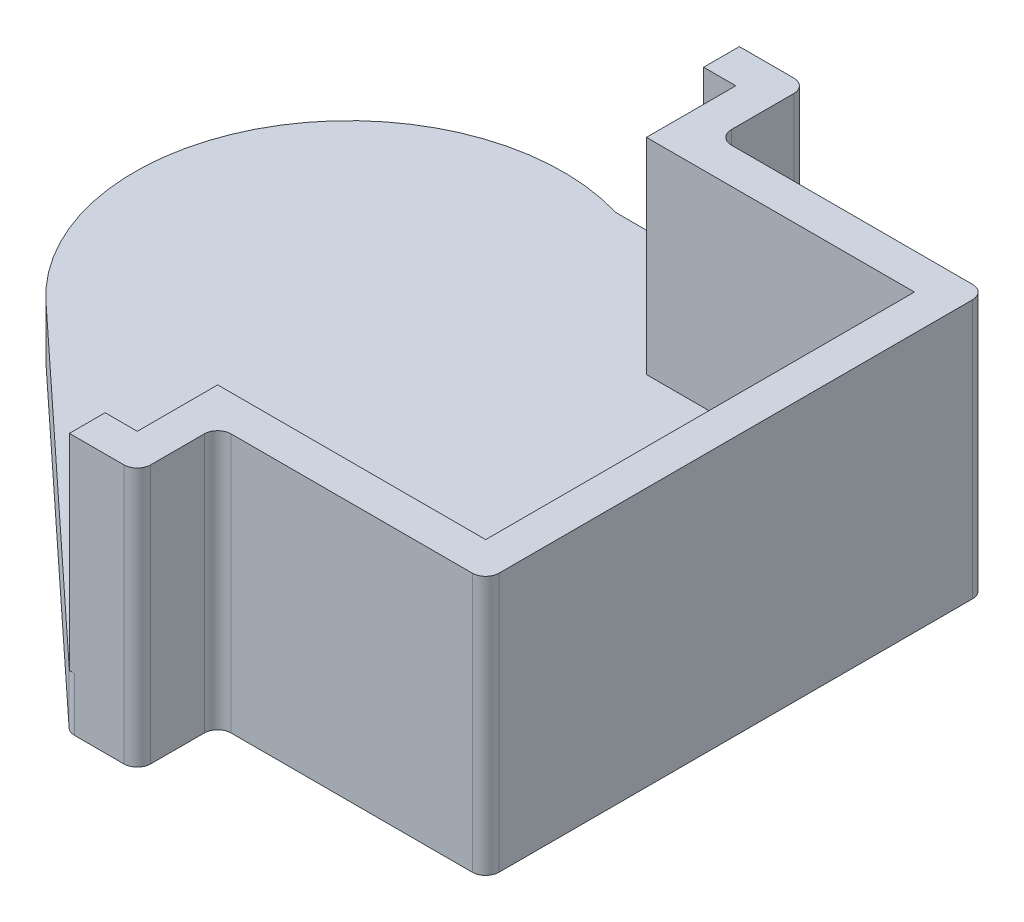
SolidWorks part; units mm, degrees
ref_plane "Front Plane" through (0, 0, 0) normal (0, 0, 1) x (1, 0, 0)
ref_plane "Top Plane" through (0, 0, 0) normal (0, 1, 0) x (1, 0, 0)
ref_plane "Right Plane" through (0, 0, 0) normal (1, 0, 0) x (0, 0, -1)
sketch "Sketch1" plane through (0, 0, 0) normal (0, 1, 0) x (1, 0, 0)
  line L0 (3.35, 28) -> (3.35, 23)
  line L9 (0, 0) -> (3.35, 0)
  line L10 (0, 0) -> (0, 23)
  line L11 (0, 23) -> (3.35, 23)
  line L12 (19.65, 0) -> (19.65, 23)
  line L14 (4.65, 0) -> (4.65, -5)
  line L15 (4.65, -5) -> (3.35, -5)
  line L16 (3.35, 0) -> (3.35, -5)
  line L17 (4.65, -5) -> (3.35, -5)
  line L18 (4.65, -5) -> (4.65, 28) construction
  line L19 (4.65, 28) -> (3.35, 28)
  line L20 (3.35, -5) -> (3.35, 28) construction
  line L21 (4.65, 28) -> (4.65, 23)
  line L22 (4.65, 0) -> (19.65, 0)
  line L23 (4.65, 23) -> (19.65, 23)
  line L24 (2.85, 28) -> (2.85, 23.5)
  line L25 (-0.5, 23.5) -> (2.85, 23.5)
  line L26 (-0.5, -0.5) -> (-0.5, 23.5)
  line L27 (-0.5, -0.5) -> (2.85, -0.5)
  line L28 (2.85, -0.5) -> (2.85, -5)
  line L29 (5.15, -0.5) -> (5.15, -5)
  line L30 (5.15, -0.5) -> (20.15, -0.5)
  line L31 (20.15, -0.5) -> (20.15, 23.5)
  line L32 (5.15, 23.5) -> (20.15, 23.5)
  line L33 (5.15, 28) -> (5.15, 23.5)
  line L34 (4.65, -4.5) -> (3.35, -4.5)
  line L35 (4.65, -4.5) -> (3.35, -4.5)
  line L37 (5.15, -5) -> (5.15, 28)
  line L38 (3.85, -5) -> (3.85, 28)
  line L39 (2.85, -5) -> (3.35, -5)
  line L40 (5.15, -5) -> (4.65, -5)
  line L41 (3.35, 28) -> (5.15, 28)
  line L42 (4.65, 28) -> (3.35, 28)
  line L43 (5.15, 28) -> (5.15, 28.5)
  line L46 (2.85, 28) -> (2.85, 28.5)
  line L47 (2.85, 28.5) -> (5.15, 28.5)
  line L48 (5.15, 28) -> (5.15, 28.5)
  dimension "D1" = 23
  dimension "D2" = 19.65
  dimension "D3" = 15
  dimension "D4" = 1.3
  dimension "D5" = 5
  dimension "D6" = 5
  dimension "D7" = 0.5
sketch "Sketch3" plane through (0, 0, 0) normal (0, 1, 0) x (1, 0, 0)
  line L1 (3.35, -5) -> (7.15, -5)
  line L2 (3.35, -5) -> (3.35, 28)
  line L3 (3.35, 28) -> (7.15, 28)
  line L4 (7.15, -5) -> (7.15, -2.5)
  line L5 (4.65, 28) -> (3.35, 28) construction
  line L6 (7.15, 25.5) -> (7.15, 28)
  line L7 (4.65, -5) -> (3.35, -5) construction
  line L8 (7.15, 25.5) -> (22.15, 25.5)
  line L10 (7.15, -2.5) -> (22.15, -2.5)
  line L11 (22.15, 25.5) -> (22.15, -2.5)
  line L12 (4.65, 23) -> (19.65, 23) construction
  line L13 (19.65, 0) -> (19.65, 23) construction
  line L14 (4.65, 0) -> (19.65, 0) construction
  line L15 (4.65, 0) -> (4.65, -5) construction
  point P20 (7.15, -3.75)
  dimension "D1" = 2.5
  dimension "D2" = 2.5
  dimension "D3" = 2.5
  dimension "D4" = 2.5
sketch "Sketch9" plane through (0, 0, 0) normal (0, 1, 0) x (1, 0, 0)
  line L0 (3.35, 28) -> (3.35, 23)
  line L9 (0, 0) -> (3.35, 0)
  line L10 (0, 0) -> (0, 23)
  line L11 (0, 23) -> (3.35, 23)
  line L12 (19.65, 0) -> (19.65, 23)
  line L14 (4.65, 0) -> (4.65, -4.5)
  line L15 (4.65, -5) -> (3.35, -5)
  line L16 (3.35, 0) -> (3.35, -4.5)
  line L17 (4.65, -5) -> (3.35, -5)
  line L18 (4.65, -4.5) -> (4.65, 28) construction
  line L19 (4.65, 28) -> (3.35, 28)
  line L20 (3.35, -4.5) -> (3.35, 28) construction
  line L21 (4.65, 28) -> (4.65, 23)
  line L22 (4.65, 0) -> (19.65, 0)
  line L23 (4.65, 23) -> (19.65, 23)
  line L24 (4.65, 28) -> (3.35, 28)
  line L25 (5.15, -5) -> (3.35, -5)
  line L26 (7.15, -5) -> (7.15, -6.25)
  line L27 (6.4, -7) -> (3.35, -7)
  line L28 (3.35, -5) -> (3.35, -7)
  line L29 (5.15, -0.5) -> (5.15, -5)
  line L30 (5.15, -0.5) -> (20.15, -0.5)
  line L31 (20.15, -0.5) -> (20.15, 23.5)
  line L32 (5.15, 23.5) -> (20.15, 23.5)
  line L33 (5.15, 28) -> (5.15, 23.5)
  line L34 (4.65, -4.5) -> (3.35, -4.5)
  line L35 (4.65, -4.5) -> (3.35, -4.5)
  line L36 (7.15, 28) -> (7.15, 26.25)
  line L37 (5.15, -5) -> (5.15, -0.5)
  line L38 (3.35, -5) -> (3.35, -7)
  line L40 (5.15, -5) -> (4.65, -5)
  line L41 (3.35, 28) -> (4.65, 28)
  line L42 (4.65, 28) -> (3.35, 28)
  line L43 (5.15, 28) -> (5.15, 28.5)
  line L47 (3.35, 30.5) -> (5.15, 30.5)
  line L48 (5.15, 28) -> (5.15, 28.5)
  line L49 (7.9, 25.5) -> (21.4, 25.5)
  line L50 (22.15, -1.75) -> (22.15, 24.75)
  line L51 (7.9, -2.5) -> (21.4, -2.5)
  line L52 (7.15, -3.25) -> (7.15, -5)
  line L53 (5.15, 23.5) -> (5.15, 28)
  line L54 (7.15, 28) -> (7.15, 29.75)
  line L55 (6.4, 30.5) -> (3.35, 30.5)
  line L57 (5.15, -5) -> (5.15, 28) construction
  line L58 (7.15, -2.5) -> (22.15, -2.5) construction
  line L60 (3.35, 30.5) -> (5.15, 30.5)
  line L61 (3.35, 30.5) -> (3.35, 28.5)
  line L62 (3.35, 28.5) -> (5.15, 28.5)
  line L64 (4.65, 0) -> (4.65, -5) construction
  line L65 (4.65, -5) -> (4.65, 28) construction
  line L66 (7.15, -2.5) -> (7.15, -5) construction
  line L67 (7.15, 28) -> (7.15, 25.5) construction
  line L68 (7.15, 25.5) -> (22.15, 25.5) construction
  line L69 (22.15, -2.5) -> (22.15, 25.5) construction
  arc A0 (7.9, -2.5) -> (7.15, -3.25) centre (7.9, -3.25) ccw
  arc A1 (7.15, 26.25) -> (7.9, 25.5) centre (7.9, 26.25) ccw
  arc A2 (7.15, 29.75) -> (6.4, 30.5) centre (6.4, 29.75) ccw
  arc A3 (21.4, 25.5) -> (22.15, 24.75) centre (21.4, 24.75) cw
  arc A4 (22.15, -1.75) -> (21.4, -2.5) centre (21.4, -1.75) cw
  arc A5 (7.15, -6.25) -> (6.4, -7) centre (6.4, -6.25) cw
  dimension "D10" = 0.75
  dimension "D1" = 23
  dimension "D2" = 19.65
  dimension "D3" = 15
  dimension "D4" = 1.3
  dimension "D5" = 5
  dimension "D6" = 5
  dimension "D7" = 0.5
  dimension "D8" = 2.5
  dimension "D9" = 2
  dimension "D11" = 0.5
extrude "Bracket" add sketch "Sketch9" along normal blind 11.5 contours L61 L62 L43 L33 L32 L31 L30 L29 L25 L15 L28 L27 L26 L52 L51 L50 L49 L36 L54 L55 L47
sketch "Sketch12" plane through (0, 0, 0) normal (0, 1, 0) x (1, 0, 0)
  line L0 (3.1341, -6.7994) -> (-15.1691, 10.209)
  line L2 (-3.4667, 30.5) -> (6.4, 30.5)
  line L3 (7.15, 29.75) -> (7.15, 26.25)
  line L4 (7.9, 25.5) -> (21.4, 25.5)
  line L5 (22.15, 24.75) -> (22.15, -1.75)
  line L6 (21.4, -2.5) -> (7.9, -2.5)
  line L7 (7.15, -3.25) -> (7.15, -6.25)
  line L8 (6.4, -7) -> (3.6447, -7)
  arc A0 (-3.6746, 30.5294) -> (-15.1691, 10.209) centre (-7.0005, 18.9995) ccw
  arc A1 (3.1341, -6.7994) -> (3.6447, -7) centre (3.6447, -6.25) ccw
  arc A2 (7.15, -6.25) -> (6.4, -7) centre (6.4, -6.25) cw
  arc A3 (7.9, -2.5) -> (7.15, -3.25) centre (7.9, -3.25) ccw
  arc A4 (22.15, -1.75) -> (21.4, -2.5) centre (21.4, -1.75) cw
  arc A5 (21.4, 25.5) -> (22.15, 24.75) centre (21.4, 24.75) cw
  arc A6 (7.15, 26.25) -> (7.9, 25.5) centre (7.9, 26.25) ccw
  arc A7 (6.4, 30.5) -> (7.15, 29.75) centre (6.4, 29.75) cw
  arc A8 (-3.4667, 30.5) -> (-3.6746, 30.5294) centre (-3.4667, 31.25) cw
  point P17 (3.35, -7)
  point P22 (7.15, -2.5)
  point P25 (22.15, -2.5)
  point P28 (22.15, 25.5)
  point P31 (7.15, 25.5)
  dimension "D1" = 0.75
extrude "Boss-Extrude1" add sketch "Sketch12" against normal blind 3
